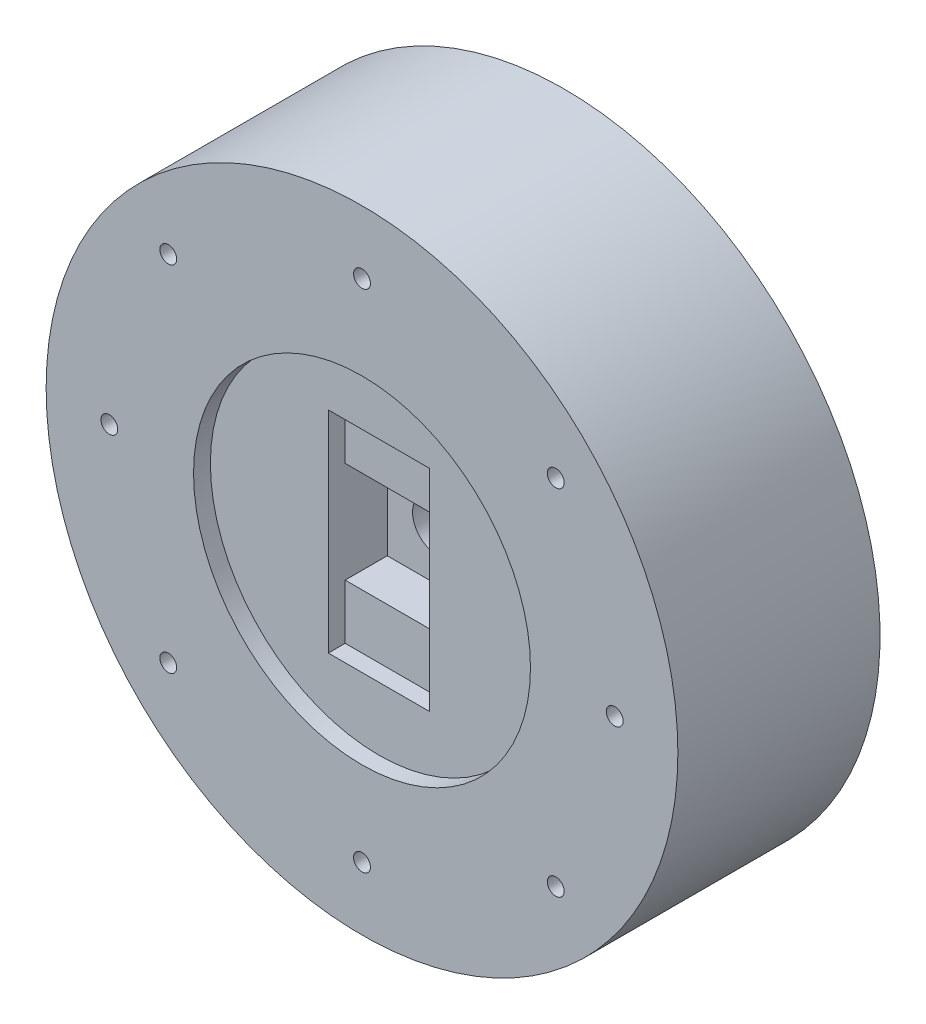
SolidWorks part; units mm, degrees
ref_plane "Спереди" through (0, 0, 0) normal (0, 0, 1) x (1, 0, 0)
ref_plane "Сверху" through (0, 0, 0) normal (0, 1, 0) x (1, 0, 0)
ref_plane "Справа" through (0, 0, 0) normal (1, 0, 0) x (0, 0, -1)
sketch "Эскиз1" plane through (0, 0, 0) normal (0, 0, 1) x (1, 0, 0)
  circle A0 centre (0, 0) radius 37.5
  circle A1 centre (0, 0) radius 3
  dimension "D1" = 75
extrude "Бобышка-Вытянуть1" add sketch "Эскиз1" along normal blind 5
sketch "Эскиз2" plane through (0, 0, 0) normal (0, 0, -1) x (-1, 0, 0)
  circle A0 centre (0, 0) radius 37.5
  dimension "D1" = 75
extrude "Бобышка-Вытянуть2" add sketch "Эскиз2" along normal blind 10
sketch "Эскиз3" plane through (0, 0, 5) normal (0, 0, 1) x (1, 0, 0)
  line L1 (-6, -6) -> (6, -6)
  line L2 (-6, -6) -> (-6, 6)
  line L3 (-6, 6) -> (6, 6)
  line L4 (6, -6) -> (6, 6)
  line L5 (0, 6) -> (0, -6) construction
  line L6 (-6, 0) -> (6, 0) construction
  circle A0 centre (0, 0) radius 37.5
  circle A1 centre (0, 30) radius 1
  circle A2 centre (0, -30) radius 1
  circle A3 centre (-30, 0) radius 1
  circle A4 centre (30, 0) radius 1
  circle A5 centre (-23, 21) radius 1
  circle A6 centre (-23, -21) radius 1
  circle A7 centre (23, -21) radius 1
  circle A8 centre (23, 21) radius 1
  dimension "D3" = 75
  dimension "D1" = 12
  dimension "D2" = 12
extrude "Бобышка-Вытянуть3" add sketch "Эскиз3" along normal blind 5
sketch "Эскиз4" plane through (0, 0, 10) normal (0, 0, 1) x (1, 0, 0)
  line L1 (-6, -12.5) -> (6, -12.5)
  line L2 (-6, -12.5) -> (-6, 12.5)
  line L3 (-6, 12.5) -> (6, 12.5)
  line L4 (6, -12.5) -> (6, 12.5)
  line L5 (0, 12.5) -> (0, -12.5) construction
  line L6 (-6, 0) -> (6, 0) construction
  circle A0 centre (0, 0) radius 37.5
  circle A1 centre (0, 30) radius 1
  circle A2 centre (0, -30) radius 1
  circle A3 centre (-30, 0) radius 1
  circle A4 centre (30, 0) radius 1
  circle A5 centre (-23, -21) radius 1
  circle A6 centre (23, -21) radius 1
  circle A7 centre (-23, 21) radius 1
  circle A8 centre (23, 21) radius 1
  dimension "D1" = 75
  dimension "D2" = 25
extrude "Бобышка-Вытянуть4" add sketch "Эскиз4" along normal blind 2
sketch "Эскиз5" plane through (0, 0, 12) normal (0, 0, 1) x (1, 0, 0)
  circle A0 centre (0, 0) radius 20
  circle A1 centre (0, 0) radius 37.5
  circle A2 centre (0, 30) radius 1
  circle A3 centre (0, -30) radius 1
  circle A4 centre (-30, 0) radius 1
  circle A5 centre (30, 0) radius 1
  circle A7 centre (-23, 21) radius 1
  circle A8 centre (23, 21) radius 1
  circle A9 centre (-23, -21) radius 1
  circle A10 centre (23, -21) radius 1
  dimension "D1" = 40
extrude "Бобышка-Вытянуть5" add sketch "Эскиз5" along normal blind 2
